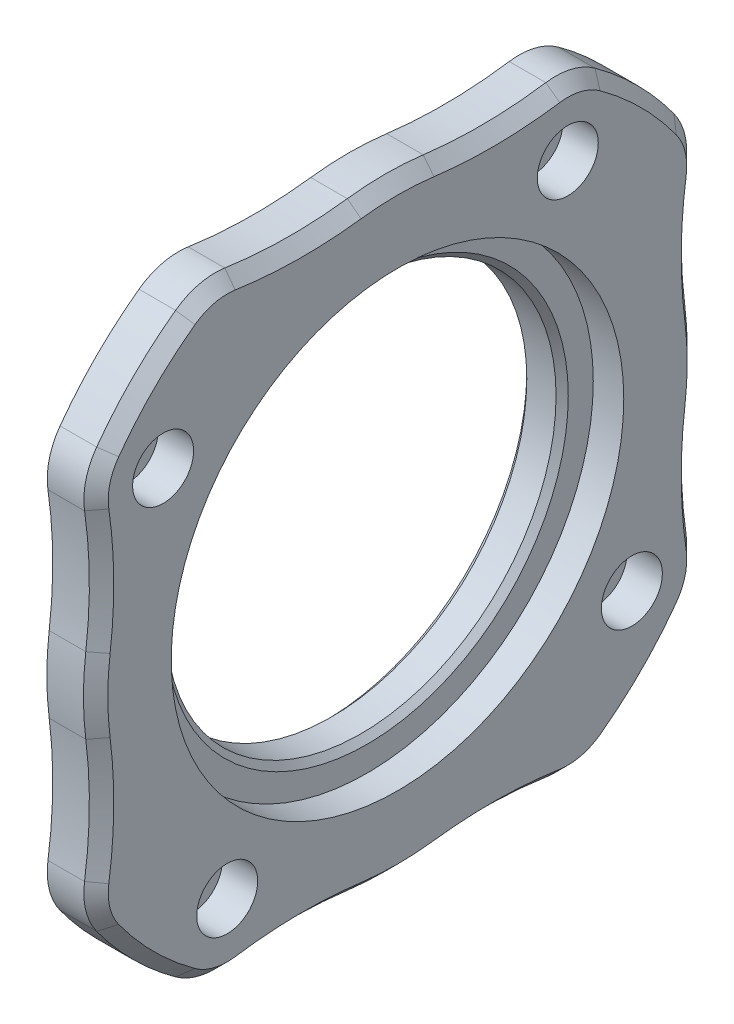
SolidWorks part; units mm, degrees
ref_plane "前视基准面" through (0, 0, 0) normal (1, 0, 0) x (0, 1, 0)
ref_plane "上视基准面" through (0, 0, 0) normal (0, 0, 1) x (0, 1, 0)
ref_plane "右视基准面" through (0, 0, 0) normal (0, 1, 0) x (-1, 0, 0)
other "Configuration Table"
sketch "草图1" plane through (0, 0, 0) normal (1, 0, 0) x (0, 1, 0)
  circle A0 centre (0, 0) radius 30
  dimension "D1" = 60
extrude "凸台-拉伸1" add sketch "草图1" along normal blind 4
sketch "草图2" plane through (0, 0, 0) normal (-1, 0, 0) x (0, -1, 0)
  line L0 (0, 30) -> (0, 0) construction
  line L1 (0, 0) -> (-30, 0) construction
  line L3 (-13.9599, -19.2142) -> (0, 0) construction
  line L4 (0, 0) -> (-21.2132, -21.2132) construction
  arc A0 (-15.4294, -21.2367) -> (-13.5954, -21.6874) centre (-13.9599, -19.2142) ccw
  arc A1 (-2.7345, -21.5774) -> (-13.5954, -21.6874) centre (-7.7635, -61.26) ccw
  arc A2 (-2.7345, -21.5774) -> (2.7345, -21.5774) centre (0, 0) ccw
  arc A3 (-21.2367, -15.4294) -> (-15.4294, -21.2367) centre (0, 0) ccw
  arc A4 (-21.2367, -15.4294) -> (-21.6874, -13.5954) centre (-19.2142, -13.9599) cw
  arc A5 (-21.5774, -2.7345) -> (-21.6874, -13.5954) centre (-61.26, -7.7635) cw
  arc A6 (-21.5774, -2.7345) -> (-21.5774, 2.7345) centre (0, 0) cw
  arc A7 (-21.5774, 2.7345) -> (-21.6874, 13.5954) centre (-61.26, 7.7635) ccw
  arc A8 (-21.2367, 15.4294) -> (-21.6874, 13.5954) centre (-19.2142, 13.9599) ccw
  arc A9 (-21.2367, 15.4294) -> (-15.4294, 21.2367) centre (0, 0) cw
  arc A10 (-15.4294, 21.2367) -> (-13.5954, 21.6874) centre (-13.9599, 19.2142) cw
  arc A11 (-2.7345, 21.5774) -> (-13.5954, 21.6874) centre (-7.7635, 61.26) cw
  arc A12 (-2.7345, 21.5774) -> (2.7345, 21.5774) centre (0, 0) cw
  arc A13 (15.4294, 21.2367) -> (13.5954, 21.6874) centre (13.9599, 19.2142) ccw
  arc A14 (2.7345, 21.5774) -> (13.5954, 21.6874) centre (7.7635, 61.26) ccw
  arc A15 (21.2367, 15.4294) -> (15.4294, 21.2367) centre (0, 0) ccw
  arc A16 (21.2367, 15.4294) -> (21.6874, 13.5954) centre (19.2142, 13.9599) cw
  arc A17 (21.5774, 2.7345) -> (21.6874, 13.5954) centre (61.26, 7.7635) cw
  arc A18 (21.5774, -2.7345) -> (21.5774, 2.7345) centre (0, 0) ccw
  arc A19 (21.5774, -2.7345) -> (21.6874, -13.5954) centre (61.26, -7.7635) ccw
  arc A20 (21.2367, -15.4294) -> (21.6874, -13.5954) centre (19.2142, -13.9599) ccw
  arc A21 (21.2367, -15.4294) -> (15.4294, -21.2367) centre (0, 0) cw
  arc A22 (15.4294, -21.2367) -> (13.5954, -21.6874) centre (13.9599, -19.2142) cw
  arc A23 (2.7345, -21.5774) -> (13.5954, -21.6874) centre (7.7635, -61.26) cw
  circle A24 centre (0, 0) radius 30 construction
  dimension "D1" = 2.5
  dimension "D4" = 40
  dimension "D5" = 26.25
  dimension "D6" = 21.75
  dimension "D2" = 54
  dimension "D3" = 45
extrude "凸台-拉伸2" add sketch "草图2" along normal blind 1.9
chamfer "倒角1" distance 1 angle 45 24 edges at (0, -18.5616, -18.5616) (0, -21.6419, -14.5566) (0, -14.5566, -21.6419) (0, -21.2621, -8.1687) (0, -8.1687, -21.2621) (0, -21.75, 0) (0, 0, -21.75) (0, -21.2621, 8.1687) (0, 8.1687, -21.2621) (0, -21.6419, 14.5566) (0, 14.5566, -21.6419) (0, -18.5616, 18.5616) (0, 18.5616, -18.5616) (0, -14.5566, 21.6419) (0, 21.6419, -14.5566) (0, -8.1687, 21.2621) (0, 21.2621, -8.1687) (0, 0, 21.75) (0, 21.75, 0) (0, 8.1687, 21.2621) (0, 21.2621, 8.1687) (0, 14.5566, 21.6419) (0, 21.6419, 14.5566) (0, 18.5616, 18.5616)
sketch "草图5" plane through (4, 0, 0) normal (1, 0, 0) x (0, 1, 0)
  circle A0 centre (0, 0) radius 16
  dimension "D1" = 32
extrude "切除-拉伸2" cut sketch "草图5" against normal through all
sketch "草图6" plane through (4, 0, 0) normal (1, 0, 0) x (0, 1, 0)
  line L0 (0, 0) -> (23.75, 0) construction
  line L1 (0, 0) -> (0, 23.75) construction
  line L2 (13.9599, 19.2142) -> (0, 0) construction
  circle A0 centre (0, 0) radius 23.75 construction
  point P4 (13.9599, 19.2142)
  point P12 (19.2142, -13.9599)
  point P14 (-13.9599, -19.2142)
  point P16 (-19.2142, 13.9599)
  point P19 (-13.9599, 19.2142) [skipped]
  point P23 (-19.2142, -13.9599) [skipped]
  point P25 (13.9599, -19.2142) [skipped]
  dimension "D1" = 47.5
  dimension "D2" = 36
  dimension "D4" = 4
hole_wizard "M2.5 六角圆柱头螺钉的柱形沉头孔1" positions "草图6" profile "草图7" counterbore size "M2.5" standard "GB"
sketch "草图7" plane through (4, -19.2142, 13.9599) normal (0, 1, 0) x (0, 0, -1)
  line L0 (0, 0) -> (0, 5.9)
  line L1 (0, 5.9) -> (1.35, 5.9)
  line L3 (1.35, 5.9) -> (1.35, 2.9)
  line L4 (1.35, 2.9) -> (2.5, 2.9)
  line L5 (2.5, 2.9) -> (2.5, 0)
  line L7 (2.5, 0) -> (0, 0)
  line L11 (0, -6.35) -> (0, 107.95) construction
  dimension "通孔孔直径" = 2.7
  dimension "通孔孔深度" = 5.9
  dimension "柱形沉头孔直径" = 5
  dimension "柱形沉头孔深度" = 2.9
sketch "草图8" plane through (4, 0, 0) normal (1, 0, 0) x (0, 0, -1)
  line L0 (0, 30) -> (0, 0) construction
  line L1 (0, 0) -> (-30, 0) construction
  line L2 (-13.9599, -19.2142) -> (0, 0) construction
  line L3 (0, 0) -> (-31.7925, -31.7925) construction
  arc A0 (-15.4294, -21.2367) -> (-13.5954, -21.6874) centre (-13.9599, -19.2142) ccw construction
  arc A1 (-2.7345, -21.5774) -> (-13.5954, -21.6874) centre (-7.7635, -61.26) ccw construction
  arc A2 (-2.7345, -21.5774) -> (2.7345, -21.5774) centre (0, 0) ccw construction
  arc A3 (-21.2367, -15.4294) -> (-15.4294, -21.2367) centre (0, 0) ccw construction
  arc A4 (-21.2367, -15.4294) -> (-21.6874, -13.5954) centre (-19.2142, -13.9599) cw construction
  arc A5 (-21.5774, -2.7345) -> (-21.6874, -13.5954) centre (-61.26, -7.7635) cw construction
  arc A6 (-21.5774, -2.7345) -> (-21.5774, 2.7345) centre (0, 0) cw construction
  arc A7 (-21.5774, 2.7345) -> (-21.6874, 13.5954) centre (-61.26, 7.7635) ccw construction
  arc A8 (-21.2367, 15.4294) -> (-21.6874, 13.5954) centre (-19.2142, 13.9599) ccw construction
  arc A9 (-21.2367, 15.4294) -> (-15.4294, 21.2367) centre (0, 0) cw construction
  arc A10 (-15.4294, 21.2367) -> (-13.5954, 21.6874) centre (-13.9599, 19.2142) cw construction
  arc A11 (-2.7345, 21.5774) -> (-13.5954, 21.6874) centre (-7.7635, 61.26) cw construction
  arc A12 (-2.7345, 21.5774) -> (2.7345, 21.5774) centre (0, 0) cw construction
  arc A13 (15.4294, 21.2367) -> (13.5954, 21.6874) centre (13.9599, 19.2142) ccw construction
  arc A14 (2.7345, 21.5774) -> (13.5954, 21.6874) centre (7.7635, 61.26) ccw construction
  arc A15 (21.2367, 15.4294) -> (15.4294, 21.2367) centre (0, 0) ccw construction
  arc A16 (21.2367, 15.4294) -> (21.6874, 13.5954) centre (19.2142, 13.9599) cw construction
  arc A17 (21.5774, 2.7345) -> (21.6874, 13.5954) centre (61.26, 7.7635) cw construction
  arc A18 (21.5774, -2.7345) -> (21.5774, 2.7345) centre (0, 0) ccw construction
  arc A19 (21.5774, -2.7345) -> (21.6874, -13.5954) centre (61.26, -7.7635) ccw construction
  arc A20 (21.2367, -15.4294) -> (21.6874, -13.5954) centre (19.2142, -13.9599) ccw construction
  arc A21 (21.2367, -15.4294) -> (15.4294, -21.2367) centre (0, 0) cw construction
  arc A22 (15.4294, -21.2367) -> (13.5954, -21.6874) centre (13.9599, -19.2142) cw construction
  arc A23 (2.7345, -21.5774) -> (13.5954, -21.6874) centre (7.7635, -61.26) cw construction
  circle A24 centre (0, 0) radius 30 construction
  arc A25 (-3.1117, 24.5536) -> (-13.158, 24.6554) centre (-7.7635, 61.26) cw
  arc A26 (-17.1927, 23.6637) -> (-13.158, 24.6554) centre (-13.9599, 19.2142) cw
  arc A27 (-23.6637, 17.1927) -> (-17.1927, 23.6637) centre (0, 0) cw
  arc A28 (-23.6637, 17.1927) -> (-24.6554, 13.158) centre (-19.2142, 13.9599) ccw
  arc A29 (-24.5536, 3.1117) -> (-24.6554, 13.158) centre (-61.26, 7.7635) ccw
  arc A30 (-24.5536, -3.1117) -> (-24.5536, 3.1117) centre (0, 0) cw
  arc A31 (-24.5536, -3.1117) -> (-24.6554, -13.158) centre (-61.26, -7.7635) cw
  arc A32 (-23.6637, -17.1927) -> (-24.6554, -13.158) centre (-19.2142, -13.9599) cw
  arc A33 (-23.6637, -17.1927) -> (-17.1927, -23.6637) centre (0, 0) ccw
  arc A34 (-17.1927, -23.6637) -> (-13.158, -24.6554) centre (-13.9599, -19.2142) ccw
  arc A35 (-3.1117, -24.5536) -> (-13.158, -24.6554) centre (-7.7635, -61.26) ccw
  arc A36 (-3.1117, -24.5536) -> (3.1117, -24.5536) centre (0, 0) ccw
  arc A37 (3.1117, -24.5536) -> (13.158, -24.6554) centre (7.7635, -61.26) cw
  arc A38 (17.1927, -23.6637) -> (13.158, -24.6554) centre (13.9599, -19.2142) cw
  arc A39 (23.6637, -17.1927) -> (17.1927, -23.6637) centre (0, 0) cw
  arc A40 (23.6637, -17.1927) -> (24.6554, -13.158) centre (19.2142, -13.9599) ccw
  arc A41 (24.5536, -3.1117) -> (24.6554, -13.158) centre (61.26, -7.7635) ccw
  arc A42 (24.5536, -3.1117) -> (24.5536, 3.1117) centre (0, 0) ccw
  arc A43 (24.5536, 3.1117) -> (24.6554, 13.158) centre (61.26, 7.7635) cw
  arc A44 (23.6637, 17.1927) -> (24.6554, 13.158) centre (19.2142, 13.9599) cw
  arc A45 (23.6637, 17.1927) -> (17.1927, 23.6637) centre (0, 0) ccw
  arc A46 (17.1927, 23.6637) -> (13.158, 24.6554) centre (13.9599, 19.2142) ccw
  arc A47 (3.1117, 24.5536) -> (13.158, 24.6554) centre (7.7635, 61.26) ccw
  arc A48 (-3.1117, 24.5536) -> (3.1117, 24.5536) centre (0, 0) cw
  dimension "D1" = 2.5
  dimension "D4" = 40
  dimension "D5" = 26.25
  dimension "D6" = 21.75
  dimension "D2" = 54
  dimension "D3" = 45
  dimension "D7" = 3
extrude "切除-拉伸3" cut sketch "草图8" against normal through all flip side to cut
chamfer "倒角2" distance 1 angle 45 24 edges at (4, -20.6829, -20.6829) (4, -15.2726, -24.5552) (4, -24.5552, -15.2726) (4, -8.1383, -24.2619) (4, -24.2619, -8.1383) (4, 0, -24.75) (4, -24.75, 0) (4, 8.1383, -24.2619) (4, -24.2619, 8.1383) (4, 15.2726, -24.5552) (4, -24.5552, 15.2726) (4, 20.6829, -20.6829) (4, -20.6829, 20.6829) (4, 24.5552, -15.2726) (4, -15.2726, 24.5552) (4, 24.2619, -8.1383) (4, -8.1383, 24.2619) (4, 24.75, 0) (4, 0, 24.75) (4, 24.2619, 8.1383) (4, 8.1383, 24.2619) (4, 24.5552, 15.2726) (4, 15.2726, 24.5552) (4, 20.6829, 20.6829)
sketch "草图9" plane through (4, 0, 0) normal (1, 0, 0) x (0, 0, -1)
  circle A0 centre (0, 0) radius 18.55
  dimension "D1" = 37.1
extrude "切除-拉伸4" cut sketch "草图9" against normal blind 2.5
chamfer "倒角3" distance 0.5 angle 45 2 edges at (1.5, 0, -16) (-1.9, 0, -16)
